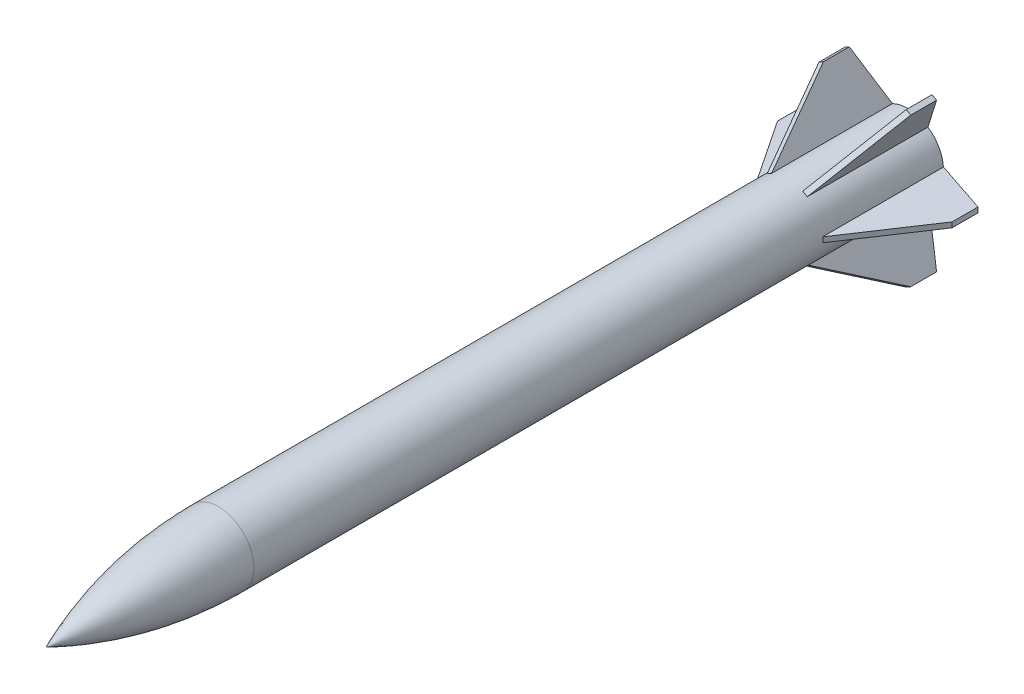
SolidWorks part; units mm, degrees
ref_plane "Front Plane" through (0, 0, 0) normal (0, 0, 1) x (1, 0, 0)
ref_plane "Top Plane" through (0, 0, 0) normal (0, 1, 0) x (1, 0, 0)
ref_plane "Right Plane" through (0, 0, 0) normal (1, 0, 0) x (0, 0, -1)
sketch "Sketch1" plane through (0, 0, 0) normal (0, 0, 1) x (1, 0, 0)
  circle A0 centre (0, 0) radius 41.3
  dimension "D1" = 82.6
extrude "Boss-Extrude1" add sketch "Sketch1" along normal blind 800
sketch "Sketch2" plane through (0, 0, 0) normal (1, 0, 0) x (0, 0, -1)
  line L0 (-800, 0) -> (-1000, 0)
  line L1 (-800, 41.3) -> (-800, -41.3) construction
  line L2 (-800, 0) -> (-800, 41.3)
  arc A0 (-800, 41.3) -> (-1000, 0) centre (-800, -463.6115) ccw
  dimension "D1" = 200
revolve "Revolve1" add sketch "Sketch2" angle 360 about L0
sketch "Sketch3" plane through (0, 0, 0) normal (0, 1, 0) x (1, 0, 0)
  line L0 (41.3, 0) -> (41.3, -140) construction
  line L1 (41.3, -800) -> (41.3, 0) construction
  line L2 (41.3, -140) -> (101.3, -50)
  line L3 (101.3, -50) -> (101.3, -20)
  line L4 (101.3, -20) -> (41.3, 0)
  line L5 (41.3, 0) -> (0, 0)
  line L6 (0, 0) -> (0, -140)
  line L7 (0, -140) -> (41.3, -140)
  dimension "D1" = 60
  dimension "D2" = 20
  dimension "D3" = 140
  dimension "D4" = 90
extrude "Boss-Extrude2" add sketch "Sketch3" along normal mid plane 6
pattern_circular "CirPattern1" count 6 over 360 about axis through (0, 0, 0) along (0, 0, 1) of "Boss-Extrude2"
